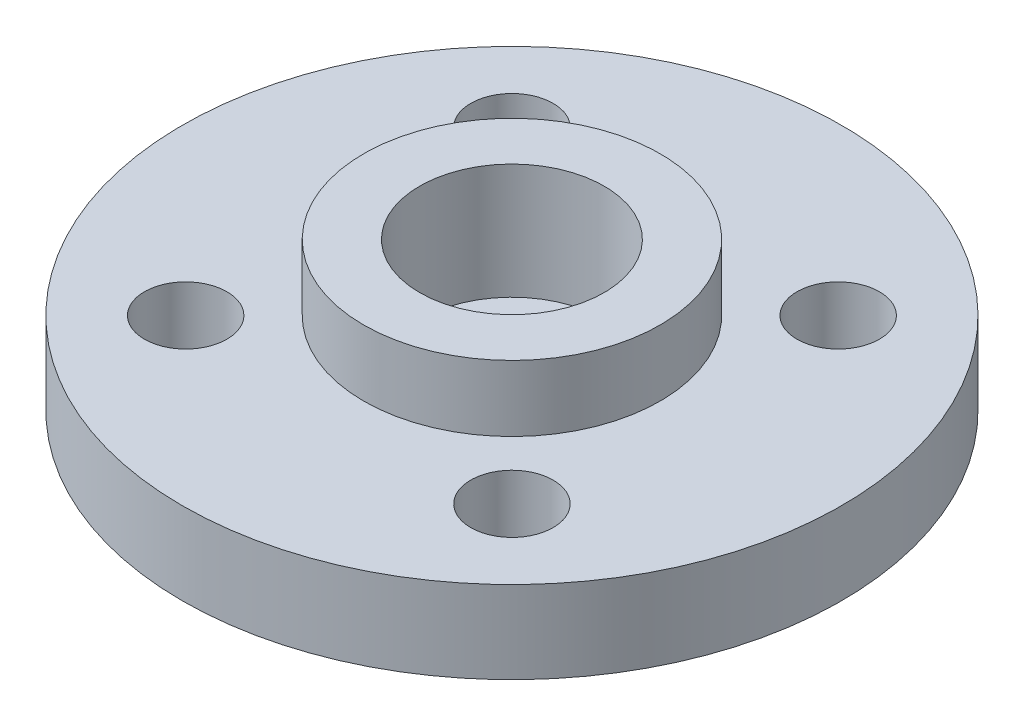
SolidWorks part; units mm, degrees
ref_plane "Plan de face" through (0, 0, 0) normal (0, 0, 1) x (1, 0, 0)
ref_plane "Plan de dessus" through (0, 0, 0) normal (0, 1, 0) x (1, 0, 0)
ref_plane "Plan de droite" through (0, 0, 0) normal (1, 0, 0) x (0, 0, -1)
sketch "Esquisse1" plane through (0, 0, 0) normal (0, 1, 0) x (1, 0, 0)
  circle A0 centre (0, 0) radius 10
  circle A1 centre (0, 0) radius 1.6
  dimension "D1" = 20
  dimension "D2" = 3.2
extrude "Boss.-Extru.1" add sketch "Esquisse1" along normal blind 2.5
sketch "Esquisse2" plane through (0, 2.5, 0) normal (0, 1, 0) x (1, 0, 0)
  circle A0 centre (0, 0) radius 2.8
  circle A1 centre (0, 0) radius 4.5
  dimension "D1" = 1.7
  dimension "D2" = 9
extrude "Boss.-Extru.2" add sketch "Esquisse2" along normal blind 2
hole_wizard "Trou pour taraudage pour trou taraudé M31" positions "Esquisse3" profile "Esquisse4" hole size "M3" standard "ISO" end condition through all
sketch "Esquisse3" plane through (0, 2.5, 0) normal (0, 1, 0) x (1, 0, 0)
  line L2 (-4.9497, 4.9497) -> (4.9497, 4.9497) construction
  line L3 (-4.9497, 4.9497) -> (-4.9497, -4.9497) construction
  line L4 (-4.9497, -4.9497) -> (4.9497, -4.9497) construction
  line L5 (4.9497, 4.9497) -> (4.9497, -4.9497) construction
  circle A0 centre (0, 0) radius 7 construction
  point P0 (4.9497, -4.9497)
  point P2 (-4.9497, -4.9497)
  point P4 (-4.9497, 4.9497)
  point P6 (4.9497, 4.9497)
  dimension "D1" = 14
sketch "Esquisse4" plane through (4.9497, 2.5, 4.9497) normal (1, 0, 0) x (0, 0, 1)
  line L0 (0, 0) -> (0, 2.5)
  line L1 (0, 2.5) -> (1.25, 2.5)
  line L2 (1.25, 2.5) -> (1.25, 0)
  line L5 (1.25, 0) -> (0, 0)
  line L11 (0, -6.35) -> (0, 107.95) construction
  dimension "Diamètre du perçage jusqu'au prochain" = 2.5
  dimension "Profondeur du perçage jusqu'au prochain" = 2.5
sketch "Esquisse5" plane through (0, 2.5, 0) normal (0, 1, 0) x (1, 0, 0)
  circle A0 centre (0, 0) radius 1.6
  circle A1 centre (0, 0) radius 2.8
  circle A2 centre (0, 0) radius 2.8 construction
  circle A3 centre (0, 0) radius 1.6 construction
extrude "Enlèv. mat.-Extru.1" cut sketch "Esquisse5" against normal blind 1.5
